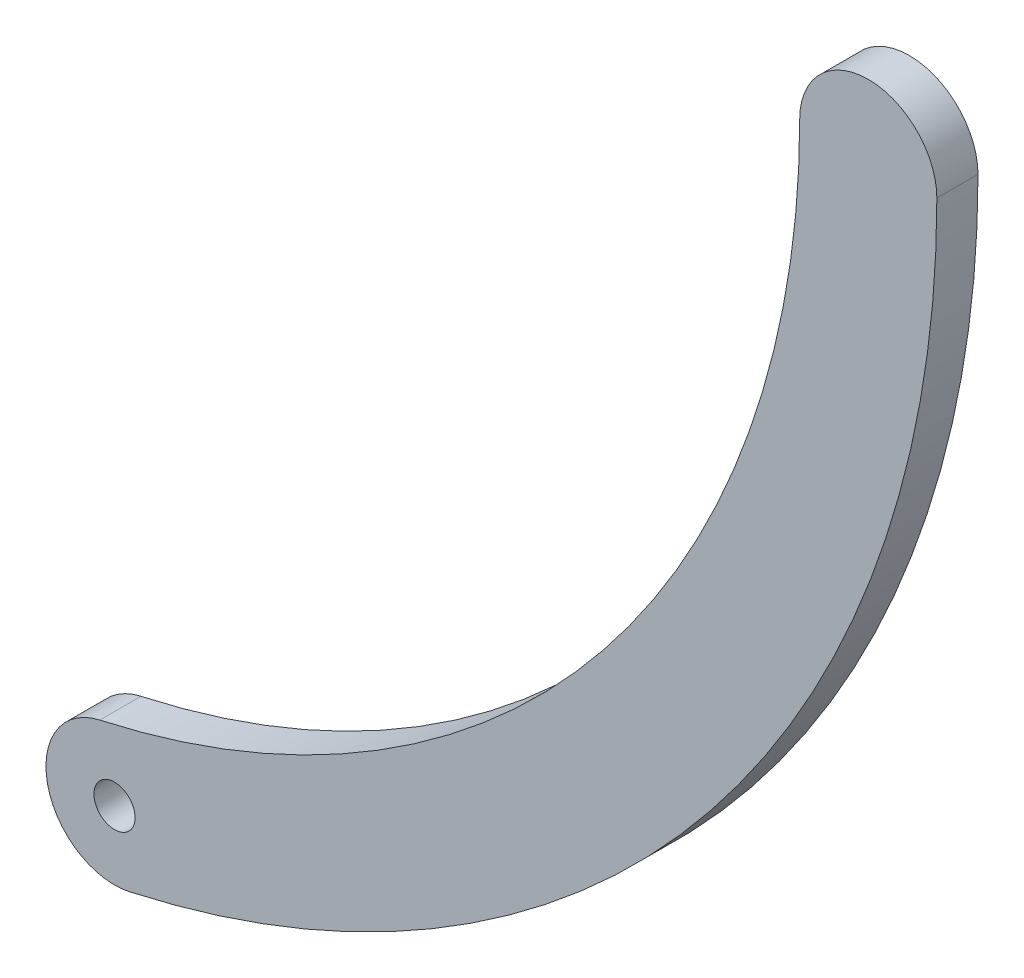
SolidWorks part; units mm, degrees
ref_plane "Alzado" through (0, 0, 0) normal (0, 0, 1) x (1, 0, 0)
ref_plane "Planta" through (0, 0, 0) normal (0, 1, 0) x (1, 0, 0)
ref_plane "Vista lateral" through (0, 0, 0) normal (1, 0, 0) x (0, 0, -1)
sketch "Croquis1" plane through (0, 0, 0) normal (0, 0, 1) x (1, 0, 0)
  line L0 (15, 0) -> (66.7509, 47.1365) construction
  line L1 (0, 0) -> (0, 68.2154) construction
  line L2 (0, 33.3929) -> (25.8852, 59.278) construction
  line L3 (0, 33.3929) -> (-14.0089, 67.2134) construction
  line L4 (-14.0089, 67.2134) -> (0, 33.3929) construction
  line L6 (0, 33.3929) -> (-14.9996, -0.1587) construction
  line L8 (25.8852, 59.278) -> (29.4207, 62.8136) construction
  line L9 (0, 68.2154) -> (70, 68.2154) construction
  line L10 (15, 0) -> (70, 68.2154) construction
  line L11 (0, 68.2154) -> (15, 0) construction
  line L12 (15, 0) -> (16.1071, -5.0346) construction
  circle A0 centre (15.0333, -0.1513) radius 1.5
  arc A1 (13.9595, 4.732) -> (65, 68.2154) centre (0, 68.2154) ccw
  arc A2 (16.1071, -5.0346) -> (75, 68.2154) centre (0, 68.2154) ccw
  arc A5 (13.9595, 4.732) -> (16.1071, -5.0346) centre (15.0333, -0.1513) ccw
  arc A8 (75, 68.2154) -> (65, 68.2154) centre (70, 68.2154) ccw
  dimension "D2" = 22.5
  dimension "D1" = 30
extrude "Saliente-Extruir1" add sketch "Croquis1" along normal blind 3
